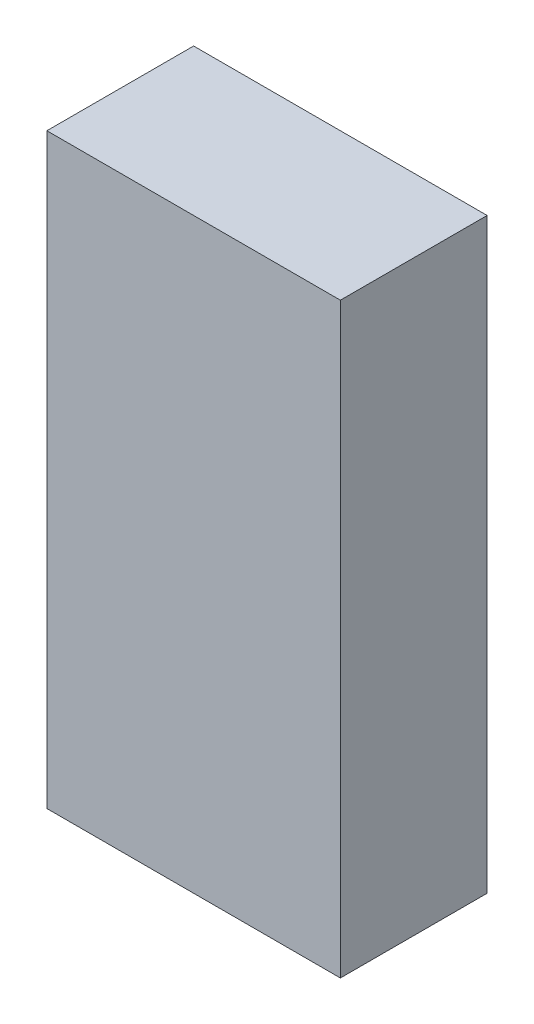
SolidWorks part; units mm, degrees
ref_plane "Alzado" through (0, 0, 0) normal (0, 0, 1) x (1, 0, 0)
ref_plane "Planta" through (0, 0, 0) normal (0, 1, 0) x (1, 0, 0)
ref_plane "Vista lateral" through (0, 0, 0) normal (1, 0, 0) x (0, 0, -1)
sketch "Croquis1" plane through (0, 0, 0) normal (0, 0, 1) x (1, 0, 0)
  line L1 (12.7, -25.4) -> (-12.7, -25.4)
  line L2 (12.7, -25.4) -> (12.7, 25.4)
  line L3 (12.7, 25.4) -> (-12.7, 25.4)
  line L4 (-12.7, -25.4) -> (-12.7, 25.4)
  line L5 (12.7, -25.4) -> (-12.7, 25.4) construction
  line L6 (12.7, 25.4) -> (-12.7, -25.4) construction
  point P0 (0, 0)
  dimension "D1" = 25.4
  dimension "D2" = 50.8
extrude "Saliente-Extruir1" add sketch "Croquis1" along normal blind 12.7
